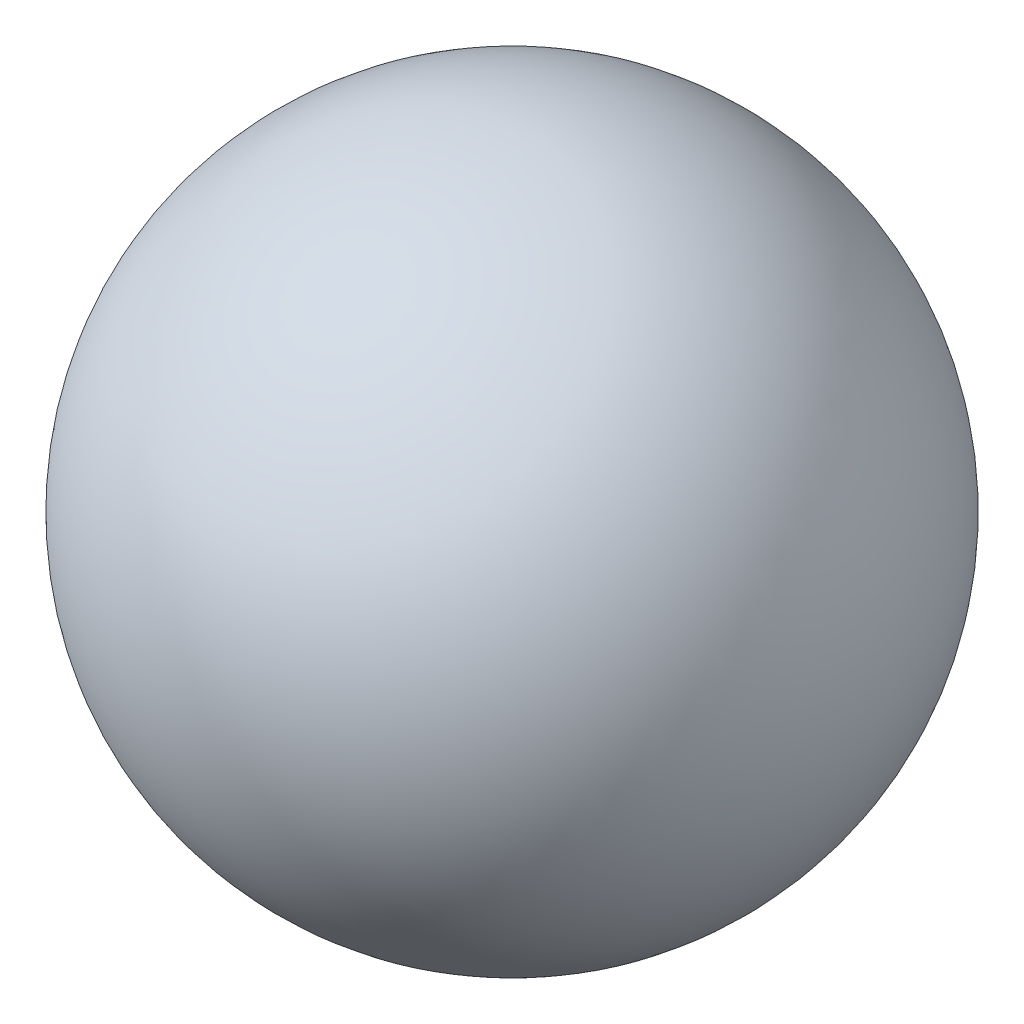
SolidWorks part; units mm, degrees
ref_plane "Alzado" through (0, 0, 0) normal (0, 0, 1) x (1, 0, 0)
ref_plane "Planta" through (0, 0, 0) normal (0, 1, 0) x (1, 0, 0)
ref_plane "Vista lateral" through (0, 0, 0) normal (1, 0, 0) x (0, 0, -1)
sketch "Croquis1" plane through (0, 0, 0) normal (0, 0, 1) x (1, 0, 0)
  line L0 (0, 15.8396) -> (0, -18.3036) construction
  line L1 (0, 25.4) -> (0, -25.4)
  arc A0 (0, -25.4) -> (0, 25.4) centre (0, 0) ccw
  dimension "D1" = 50.8
revolve "Revolución3" add sketch "Croquis1" angle 360 about L0
ref_plane "Plano1" through (25.4, 0, 0) normal (1, 0, 0) x (0, 0, -1)
sketch "Croquis4" plane through (25.4, 0, 0) normal (1, 0, 0) x (0, 0, -1)
sketch "Croquis5" plane through (0, 0, 0) normal (0, 1, 0) x (1, 0, 0)
  line L0 (0, 0) -> (25.4, 0)
  line L1 (25.4, -27.94) -> (25.4, 27.94) construction
  line L2 (0, 0) -> (0, 25.4)
  circle A0 centre (0, 0) radius 25.4 construction
  arc A1 (0, 25.4) -> (25.4, 0) centre (0, 0) cw
  dimension "D1" = 25.4
